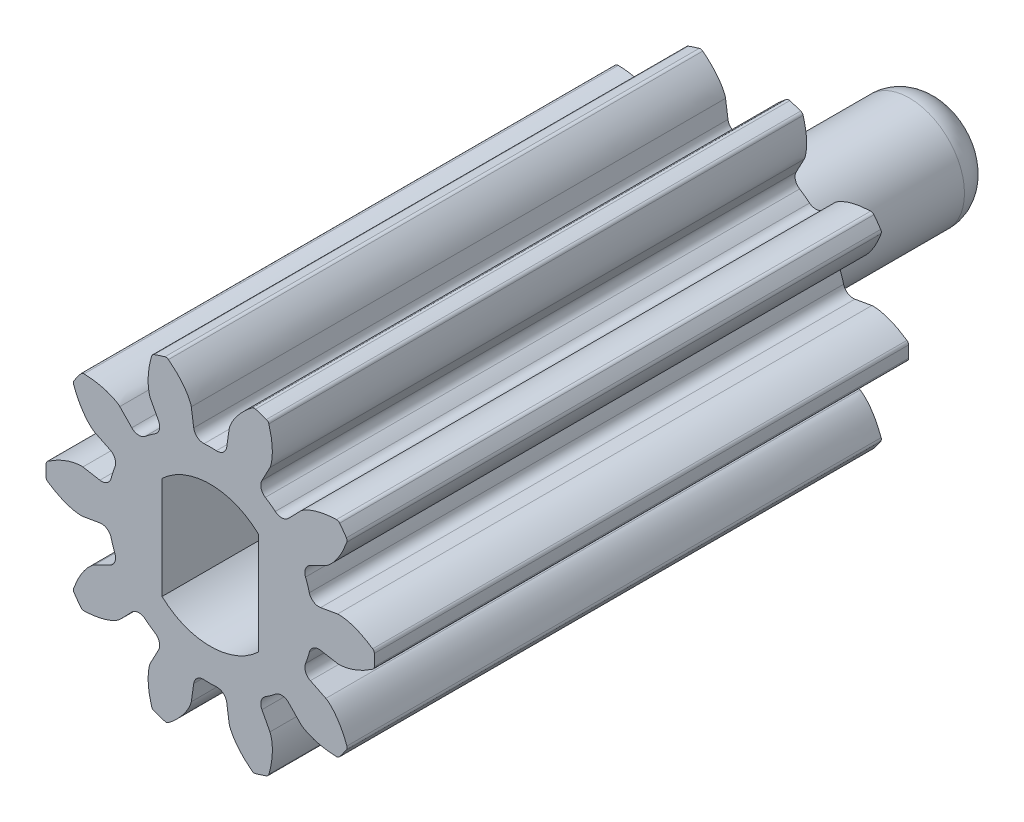
SolidWorks part; units mm, degrees
material "ABS"
ref_plane "Front" through (0, 0, 0) normal (0, 0, 1) x (1, 0, 0)
ref_plane "Top" through (0, 0, 0) normal (0, 1, 0) x (1, 0, 0)
ref_plane "Right" through (0, 0, 0) normal (1, 0, 0) x (0, 0, -1)
sketch "Sketch1" plane through (0, 0, 0) normal (0, 0, 1) x (1, 0, 0)
  circle A0 centre (0, 0) radius 6.35
extrude "Boss-Extrude1" add sketch "Sketch1" along normal blind 20.574
sketch "Sketch3" plane through (0, 0, 0) normal (0, 0, 1) x (1, 0, 0)
  line L0 (0, 0) -> (43.7181, 0) construction
  line L2 (0, 0) -> (-0.5624, 3.9287) construction
  line L3 (0, 0) -> (0.5624, 3.9287) construction
  line L4 (0.5624, 3.9287) -> (0.7046, 4.9224) construction
  line L5 (0, 0) -> (0, 61.276) construction
  line L6 (-0.5624, 3.9287) -> (-0.7046, 4.9224) construction
  circle A0 centre (0, 0) radius 6.35 construction
  circle A1 centre (0, 0) radius 5.2917 construction
  circle A2 centre (0, 0) radius 4.9725 construction
  arc A3 (0.5624, 3.9287) -> (-0.5624, 3.9287) centre (0, 0) ccw construction
  arc A5 (1.6642, 6.128) -> (-1.6642, 6.128) centre (0, 0) ccw
  spline S0 degree 4 poles (-0.7046, 4.9224) (-0.705, 4.9247) (-0.7061, 4.9311) (-0.7087, 4.9431) (-0.7137, 4.9626) (-0.721, 4.9872) (-0.7316, 5.0187) (-0.7454, 5.0554) (-0.7621, 5.0953) (-0.7818, 5.1381) (-0.8028, 5.1804) (-0.825, 5.2221) (-0.8483, 5.2631) (-0.8779, 5.3122) (-0.9151, 5.3703) (-0.9613, 5.437) (-1.0167, 5.511) (-1.0764, 5.5846) (-1.1378, 5.6556) (-1.2027, 5.7255) (-1.2676, 5.7919) (-1.338, 5.8588) (-1.4044, 5.9196) (-1.4819, 5.9855) (-1.5453, 6.0379) (-1.6323, 6.1046) (-1.6846, 6.1433) (-1.7469, 6.1876) (-1.7752, 6.2068) (-1.7925, 6.2186) knots 0 0 0 0 0 0.005377 0.015084 0.028532 0.04661 0.064855 0.092111 0.119476 0.146842 0.174209 0.201575 0.228941 0.256307 0.307035 0.361767 0.4165 0.471232 0.525964 0.580697 0.635429 0.690161 0.744894 0.799626 0.854358 0.909091 0.954545 1 1 1 1 1 construction
  spline S1 degree 4 poles (-0.7046, 4.9224) (-0.705, 4.9247) (-0.7061, 4.9311) (-0.7087, 4.9431) (-0.7137, 4.9626) (-0.721, 4.9872) (-0.7316, 5.0187) (-0.7454, 5.0554) (-0.7621, 5.0953) (-0.7818, 5.1381) (-0.8028, 5.1804) (-0.825, 5.2221) (-0.8483, 5.2631) (-0.8779, 5.3122) (-0.9151, 5.3703) (-0.9613, 5.437) (-1.0167, 5.511) (-1.0764, 5.5846) (-1.1378, 5.6556) (-1.2027, 5.7255) (-1.2676, 5.7919) (-1.338, 5.8588) (-1.4044, 5.9196) (-1.4819, 5.9855) (-1.5453, 6.0379) (-1.6134, 6.0902) (-1.647, 6.1153) (-1.6642, 6.128) knots 0 0 0 0 0 0.005377 0.015084 0.028532 0.04661 0.064855 0.092111 0.119476 0.146842 0.174209 0.201575 0.228941 0.256307 0.307035 0.361767 0.4165 0.471232 0.525964 0.580697 0.635429 0.690161 0.744894 0.799626 0.854358 0.909091 0.909091 0.909091 0.909091 0.909091
  spline S2 degree 4 poles (0.7046, 4.9224) (0.705, 4.9247) (0.7061, 4.9311) (0.7087, 4.9431) (0.7137, 4.9626) (0.721, 4.9872) (0.7316, 5.0187) (0.7454, 5.0554) (0.7621, 5.0953) (0.7818, 5.1381) (0.8028, 5.1804) (0.825, 5.2221) (0.8483, 5.2631) (0.8779, 5.3122) (0.9151, 5.3703) (0.9613, 5.437) (1.0167, 5.511) (1.0764, 5.5846) (1.1378, 5.6556) (1.2027, 5.7255) (1.2676, 5.7919) (1.338, 5.8588) (1.4044, 5.9196) (1.4819, 5.9855) (1.5453, 6.0379) (1.6323, 6.1046) (1.6846, 6.1433) (1.7469, 6.1876) (1.7752, 6.2068) (1.7925, 6.2186) knots 0 0 0 0 0 0.005377 0.015084 0.028532 0.04661 0.064855 0.092111 0.119476 0.146842 0.174209 0.201575 0.228941 0.256307 0.307035 0.361767 0.4165 0.471232 0.525964 0.580697 0.635429 0.690161 0.744894 0.799626 0.854358 0.909091 0.954545 1 1 1 1 1 construction
  spline S3 degree 4 poles (0.7046, 4.9224) (0.705, 4.9247) (0.7061, 4.9311) (0.7087, 4.9431) (0.7137, 4.9626) (0.721, 4.9872) (0.7316, 5.0187) (0.7454, 5.0554) (0.7621, 5.0953) (0.7818, 5.1381) (0.8028, 5.1804) (0.825, 5.2221) (0.8483, 5.2631) (0.8779, 5.3122) (0.9151, 5.3703) (0.9613, 5.437) (1.0167, 5.511) (1.0764, 5.5846) (1.1378, 5.6556) (1.2027, 5.7255) (1.2676, 5.7919) (1.338, 5.8588) (1.4044, 5.9196) (1.4819, 5.9855) (1.5453, 6.0379) (1.6134, 6.0902) (1.647, 6.1153) (1.6642, 6.128) knots 0 0 0 0 0 0.005377 0.015084 0.028532 0.04661 0.064855 0.092111 0.119476 0.146842 0.174209 0.201575 0.228941 0.256307 0.307035 0.361767 0.4165 0.471232 0.525964 0.580697 0.635429 0.690161 0.744894 0.799626 0.854358 0.909091 0.909091 0.909091 0.909091 0.909091
  point P0 (0, 3.9688)
sketch "DCLTBC" plane through (0, 0, 0) normal (0, 0, 1) x (1, 0, 0)
  line L0 (0, 0) -> (41.04, 0) construction
  line L1 (-0.5624, 3.9287) -> (-0.7046, 4.9224) construction
  line L2 (0.5624, 3.9287) -> (0.7046, 4.9224) construction
  line L3 (-0.5624, 3.9287) -> (-0.7046, 4.9224)
  line L4 (0.5624, 3.9287) -> (0.7046, 4.9224)
  line L5 (0, 0) -> (0, 104.9356) construction
  circle A0 centre (0, 0) radius 6.35
  circle A1 centre (0, 0) radius 5.2917 construction
  circle A2 centre (0, 0) radius 4.9725 construction
  arc A3 (0.5624, 3.9287) -> (-0.5624, 3.9287) centre (0, 0) ccw construction
  arc A4 (0.5624, 3.9287) -> (-0.5624, 3.9287) centre (0, 0) ccw
  spline S0 degree 4 poles (-988.7588, -149.038) (-11.8151, 2.4708) (-0.7866, 4.3496) (-0.6413, 4.6789) (-0.7137, 4.9626) (-0.721, 4.9872) (-0.7316, 5.0187) (-0.7454, 5.0554) (-0.7621, 5.0953) (-0.7818, 5.1381) (-0.8028, 5.1804) (-0.825, 5.2221) (-0.8483, 5.2631) (-0.8779, 5.3122) (-0.9151, 5.3703) (-0.9613, 5.437) (-1.0167, 5.511) (-1.0764, 5.5846) (-1.1378, 5.6556) (-1.2027, 5.7255) (-1.2676, 5.7919) (-1.338, 5.8588) (-1.4044, 5.9196) (-1.4819, 5.9855) (-1.8387, 6.2805) (-3.231, 7.2231) (17.05, -7.85) (-807.2758, 598.5552) knots -0.632257 -0.632257 -0.632257 -0.632257 -0.632257 0.005377 0.015084 0.028532 0.04661 0.064855 0.092111 0.119476 0.146842 0.174209 0.201575 0.228941 0.256307 0.307035 0.361767 0.4165 0.471232 0.525964 0.580697 0.635429 0.690161 0.744894 0.799626 0.854358 1.920904 1.920904 1.920904 1.920904 1.920904 only from (-0.7046, 4.9224) to (-1.6642, 6.128) construction
  spline S1 degree 4 poles (988.7588, -149.038) (11.8151, 2.4708) (0.7866, 4.3496) (0.6413, 4.6789) (0.7137, 4.9626) (0.721, 4.9872) (0.7316, 5.0187) (0.7454, 5.0554) (0.7621, 5.0953) (0.7818, 5.1381) (0.8028, 5.1804) (0.825, 5.2221) (0.8483, 5.2631) (0.8779, 5.3122) (0.9151, 5.3703) (0.9613, 5.437) (1.0167, 5.511) (1.0764, 5.5846) (1.1378, 5.6556) (1.2027, 5.7255) (1.2676, 5.7919) (1.338, 5.8588) (1.4044, 5.9196) (1.4819, 5.9855) (1.8387, 6.2805) (3.231, 7.2231) (-17.05, -7.85) (807.2758, 598.5552) knots -0.632257 -0.632257 -0.632257 -0.632257 -0.632257 0.005377 0.015084 0.028532 0.04661 0.064855 0.092111 0.119476 0.146842 0.174209 0.201575 0.228941 0.256307 0.307035 0.361767 0.4165 0.471232 0.525964 0.580697 0.635429 0.690161 0.744894 0.799626 0.854358 1.920904 1.920904 1.920904 1.920904 1.920904 only from (0.7046, 4.9224) to (1.6642, 6.128) construction
  spline S2 degree 4 poles (-0.7046, 4.9224) (-0.705, 4.9247) (-0.7061, 4.9311) (-0.7087, 4.9431) (-0.7137, 4.9626) (-0.721, 4.9872) (-0.7316, 5.0187) (-0.7454, 5.0554) (-0.7621, 5.0953) (-0.7818, 5.1381) (-0.8028, 5.1804) (-0.825, 5.2221) (-0.8483, 5.2631) (-0.8779, 5.3122) (-0.9151, 5.3703) (-0.9613, 5.437) (-1.0167, 5.511) (-1.0764, 5.5846) (-1.1378, 5.6556) (-1.2027, 5.7255) (-1.2676, 5.7919) (-1.338, 5.8588) (-1.4044, 5.9196) (-1.4819, 5.9855) (-1.5453, 6.0379) (-1.6134, 6.0902) (-1.647, 6.1153) (-1.6642, 6.128) knots 0 0 0 0 0 0.005377 0.015084 0.028532 0.04661 0.064855 0.092111 0.119476 0.146842 0.174209 0.201575 0.228941 0.256307 0.307035 0.361767 0.4165 0.471232 0.525964 0.580697 0.635429 0.690161 0.744894 0.799626 0.854358 0.909091 0.909091 0.909091 0.909091 0.909091
  spline S3 degree 4 poles (0.7046, 4.9224) (0.705, 4.9247) (0.7061, 4.9311) (0.7087, 4.9431) (0.7137, 4.9626) (0.721, 4.9872) (0.7316, 5.0187) (0.7454, 5.0554) (0.7621, 5.0953) (0.7818, 5.1381) (0.8028, 5.1804) (0.825, 5.2221) (0.8483, 5.2631) (0.8779, 5.3122) (0.9151, 5.3703) (0.9613, 5.437) (1.0167, 5.511) (1.0764, 5.5846) (1.1378, 5.6556) (1.2027, 5.7255) (1.2676, 5.7919) (1.338, 5.8588) (1.4044, 5.9196) (1.4819, 5.9855) (1.5453, 6.0379) (1.6134, 6.0902) (1.647, 6.1153) (1.6642, 6.128) knots 0 0 0 0 0 0.005377 0.015084 0.028532 0.04661 0.064855 0.092111 0.119476 0.146842 0.174209 0.201575 0.228941 0.256307 0.307035 0.361767 0.4165 0.471232 0.525964 0.580697 0.635429 0.690161 0.744894 0.799626 0.854358 0.909091 0.909091 0.909091 0.909091 0.909091
extrude "Cut-Extrude-DCLTBC" cut sketch "DCLTBC" along normal through all
fillet "Fillet-Tip-DCLTBC" radius 0.1775 2 edges at (1.6642, 6.128, 10.287) (-1.6642, 6.128, 10.287)
fillet "Fillet-Root-DCLTBC" radius 0.3551 2 edges at (-0.5624, 3.9287, 10.287) (0.5624, 3.9287, 10.287)
pattern_circular "CirPattern-DCLTBC" count 10 over 360 about axis through (0, 0, 20.574) along (0, 0, 1) of "Cut-Extrude-DCLTBC", "Fillet-Tip-DCLTBC", "Fillet-Root-DCLTBC"
sketch "DCGTBC" [suppressed] plane through (0, 0, 0) normal (0, 0, 1) x (1, 0, 0)
  line L0 (0, 0) -> (41.04, 0) construction
  line L1 (-22.6634, 1.9828) -> (0, 0) construction
  line L2 (0, 0) -> (22.6634, 1.9828) construction
  line L3 (0, 0) -> (-16.5124, 0)
  line L5 (0, 0) -> (0, 104.9356) construction
  circle A0 centre (0, 0) radius 25
  circle A1 centre (0, 0) radius 24 construction
  circle A2 centre (0, 0) radius 21.7514 construction
  arc A3 (0.0626, 22.7499) -> (-0.0626, 22.7499) centre (0, 0) ccw construction
  arc A11 (22.6634, 1.9828) -> (-22.6634, 1.9828) centre (0, 0) ccw
  spline S4 degree 4 poles (999.7589, -2.0808) (12.8658, 20.0937) (0.2547, 20.6746) (0.0189, 21.2606) (0.0654, 21.8429) (0.0715, 21.8997) (0.0812, 21.973) (0.095, 22.0592) (0.1126, 22.1539) (0.1343, 22.2566) (0.1583, 22.3589) (0.1845, 22.4607) (0.2124, 22.562) (0.2486, 22.6844) (0.2952, 22.8308) (0.3543, 23.0013) (0.4268, 23.1939) (0.5065, 23.3893) (0.5897, 23.5809) (0.6793, 23.7735) (0.7698, 23.9592) (0.8695, 24.151) (0.9643, 24.3275) (1.0767, 24.524) (1.517, 25.277) (3.0654, 27.5692) (-13.787, 0.9944) (540.7091, 867.0187) knots -0.561807 -0.561807 -0.561807 -0.561807 -0.561807 0.005377 0.015084 0.028532 0.04661 0.064855 0.092111 0.119476 0.146842 0.174209 0.201575 0.228941 0.256307 0.307035 0.361767 0.4165 0.471232 0.525964 0.580697 0.635429 0.690161 0.744894 0.799626 0.854358 1.731906 1.731906 1.731906 1.731906 1.731906 only from (0.0598, 21.7513) to (1.3455, 24.9638) construction
  spline S5 degree 4 poles (-999.7589, -2.0808) (-12.8658, 20.0937) (-0.2547, 20.6746) (-0.0189, 21.2606) (-0.0654, 21.8429) (-0.0715, 21.8997) (-0.0812, 21.973) (-0.095, 22.0592) (-0.1126, 22.1539) (-0.1343, 22.2566) (-0.1583, 22.3589) (-0.1845, 22.4607) (-0.2124, 22.562) (-0.2486, 22.6844) (-0.2952, 22.8308) (-0.3543, 23.0013) (-0.4268, 23.1939) (-0.5065, 23.3893) (-0.5897, 23.5809) (-0.6793, 23.7735) (-0.7698, 23.9592) (-0.8695, 24.151) (-0.9643, 24.3275) (-1.0767, 24.524) (-1.517, 25.277) (-3.0654, 27.5692) (13.787, 0.9944) (-540.7091, 867.0187) knots -0.561807 -0.561807 -0.561807 -0.561807 -0.561807 0.005377 0.015084 0.028532 0.04661 0.064855 0.092111 0.119476 0.146842 0.174209 0.201575 0.228941 0.256307 0.307035 0.361767 0.4165 0.471232 0.525964 0.580697 0.635429 0.690161 0.744894 0.799626 0.854358 1.731906 1.731906 1.731906 1.731906 1.731906 only from (-0.0598, 21.7513) to (-1.3455, 24.9638) construction
  spline S6 degree 4 poles (0.0598, 21.7513) (0.0599, 21.7565) (0.0603, 21.7709) (0.0618, 21.7983) (0.0654, 21.8429) (0.0715, 21.8997) (0.0812, 21.973) (0.095, 22.0592) (0.1126, 22.1539) (0.1343, 22.2566) (0.1583, 22.3589) (0.1845, 22.4607) (0.2124, 22.562) (0.2486, 22.6844) (0.2952, 22.8308) (0.3543, 23.0013) (0.4268, 23.1939) (0.5065, 23.3893) (0.5897, 23.5809) (0.6793, 23.7735) (0.7698, 23.9592) (0.8695, 24.151) (0.9643, 24.3275) (1.0767, 24.524) (1.1693, 24.6823) (1.27, 24.8447) (1.3197, 24.9235) (1.3455, 24.9638) knots 0 0 0 0 0 0.005377 0.015084 0.028532 0.04661 0.064855 0.092111 0.119476 0.146842 0.174209 0.201575 0.228941 0.256307 0.307035 0.361767 0.4165 0.471232 0.525964 0.580697 0.635429 0.690161 0.744894 0.799626 0.854358 0.909091 0.909091 0.909091 0.909091 0.909091
  spline S7 degree 4 poles (-0.0598, 21.7513) (-0.0599, 21.7565) (-0.0603, 21.7709) (-0.0618, 21.7983) (-0.0654, 21.8429) (-0.0715, 21.8997) (-0.0812, 21.973) (-0.095, 22.0592) (-0.1126, 22.1539) (-0.1343, 22.2566) (-0.1583, 22.3589) (-0.1845, 22.4607) (-0.2124, 22.562) (-0.2486, 22.6844) (-0.2952, 22.8308) (-0.3543, 23.0013) (-0.4268, 23.1939) (-0.5065, 23.3893) (-0.5897, 23.5809) (-0.6793, 23.7735) (-0.7698, 23.9592) (-0.8695, 24.151) (-0.9643, 24.3275) (-1.0767, 24.524) (-1.1693, 24.6823) (-1.27, 24.8447) (-1.3197, 24.9235) (-1.3455, 24.9638) knots 0 0 0 0 0 0.005377 0.015084 0.028532 0.04661 0.064855 0.092111 0.119476 0.146842 0.174209 0.201575 0.228941 0.256307 0.307035 0.361767 0.4165 0.471232 0.525964 0.580697 0.635429 0.690161 0.744894 0.799626 0.854358 0.909091 0.909091 0.909091 0.909091 0.909091
  dimension "D1" = 5
  dimension "D2" = 5
extrude "Cut-Extrude-DCGTBC" [suppressed] cut sketch "DCGTBC" along normal through all
fillet "Fillet-Tip-DCGTBC" [suppressed] radius 0.1775
pattern_circular "CirPattern-DCGTBC" [suppressed] count 10 over 360
sketch "Sketch4" plane through (0, 0, 20.574) normal (0, 0, 1) x (1, 0, 0)
  circle A1 centre (0, 0) radius 2.7051
  dimension "D1" = 5.4102
extrude "Cut-Extrude2" cut sketch "Sketch4" against normal through all
sketch "Sketch5" plane through (0, 0, 20.574) normal (0, 0, 1) x (1, 0, 0)
  line L0 (-1.8542, 1.9696) -> (-1.8542, -1.9696)
  line L1 (1.8542, 1.9696) -> (1.8542, -1.9696)
  circle A0 centre (0, 0) radius 2.7051 construction
  circle A1 centre (0, 0) radius 2.7051
  dimension "D1" = 3.7084
extrude "Boss-Extrude2" add sketch "Sketch5" against normal through all contours L0 A1 | L1 A1
sketch "Sketch6" plane through (0, 0, 0) normal (0, 0, -1) x (-1, 0, 0)
  line L4 (-1.9655, 2.0878) -> (-1.9655, -2.0878)
  line L5 (1.9655, -2.0878) -> (1.9655, 2.0878)
  arc A4 (-1.9655, -2.0878) -> (1.9655, -2.0878) centre (0, 0) ccw
  arc A5 (1.9655, 2.0878) -> (-1.9655, 2.0878) centre (0, 0) ccw
extrude "Boss-Extrude3" add sketch "Sketch6" against normal blind 3.175
sketch "Sketch7" plane through (0, 0, 0) normal (0, 0, -1) x (-1, 0, 0)
  circle A0 centre (0, 0) radius 2.1209
  dimension "D1" = 4.2418
extrude "Boss-Extrude4" add sketch "Sketch7" along normal blind 7.62
fillet "Fillet1" radius 1.27 1 edges at (-2.1209, 0, -7.62)
sketch "Sketch8" plane through (0, 0, 20.574) normal (0, 0, 1) x (1, 0, 0)
  line L50 (0.7297, 4.9185) -> (0.6357, 4.2621)
  line L51 (-0.6357, 4.2621) -> (-0.7297, 4.9185)
  line L52 (-2.3007, 4.4081) -> (-1.9909, 3.8218)
  line L53 (-3.0196, 3.0745) -> (-3.4814, 3.5503)
  line L54 (-4.4523, 2.2139) -> (-3.8571, 1.9217)
  line L55 (-4.25, 0.7124) -> (-4.9033, 0.8259)
  line L56 (-4.9033, -0.8259) -> (-4.25, -0.7124)
  line L57 (-3.8571, -1.9217) -> (-4.4523, -2.2139)
  line L58 (-3.4814, -3.5503) -> (-3.0196, -3.0745)
  line L59 (-1.9909, -3.8218) -> (-2.3007, -4.4081)
  line L60 (-0.7297, -4.9185) -> (-0.6357, -4.2621)
  line L61 (0.6357, -4.2621) -> (0.7297, -4.9185)
  line L62 (2.3007, -4.4081) -> (1.9909, -3.8218)
  line L63 (3.0196, -3.0745) -> (3.4814, -3.5503)
  line L64 (4.4523, -2.2139) -> (3.8571, -1.9217)
  line L65 (4.25, -0.7124) -> (4.9033, -0.8259)
  line L66 (4.9033, 0.8259) -> (4.25, 0.7124)
  line L67 (3.8571, 1.9217) -> (4.4523, 2.2139)
  line L68 (3.4814, 3.5503) -> (3.0196, 3.0745)
  line L69 (1.9909, 3.8218) -> (2.3007, 4.4081)
  line L74 (0.7297, 4.9185) -> (0.6357, 4.2621)
  line L75 (-0.6357, 4.2621) -> (-0.7297, 4.9185)
  line L76 (-2.3007, 4.4081) -> (-1.9909, 3.8218)
  line L77 (-3.0196, 3.0745) -> (-3.4814, 3.5503)
  line L78 (-4.4523, 2.2139) -> (-3.8571, 1.9217)
  line L79 (-4.25, 0.7124) -> (-4.9033, 0.8259)
  line L80 (-4.9033, -0.8259) -> (-4.25, -0.7124)
  line L81 (-3.8571, -1.9217) -> (-4.4523, -2.2139)
  line L82 (-3.4814, -3.5503) -> (-3.0196, -3.0745)
  line L83 (-1.9909, -3.8218) -> (-2.3007, -4.4081)
  line L84 (-0.7297, -4.9185) -> (-0.6357, -4.2621)
  line L85 (0.6357, -4.2621) -> (0.7297, -4.9185)
  line L86 (2.3007, -4.4081) -> (1.9909, -3.8218)
  line L87 (3.0196, -3.0745) -> (3.4814, -3.5503)
  line L88 (4.4523, -2.2139) -> (3.8571, -1.9217)
  line L89 (4.25, -0.7124) -> (4.9033, -0.8259)
  line L90 (4.9033, 0.8259) -> (4.25, 0.7124)
  line L91 (3.8571, 1.9217) -> (4.4523, 2.2139)
  line L92 (3.4814, 3.5503) -> (3.0196, 3.0745)
  line L93 (1.9909, 3.8218) -> (2.3007, 4.4081)
  arc A150 (2.1634, 5.9431) -> (1.743, 6.0797) centre (0, 0) ccw
  arc A151 (1.743, 6.0797) -> (1.6082, 6.054) centre (1.7011, 5.9334) ccw
  arc A152 (0.2363, 3.9363) -> (0.6357, 4.2621) centre (0.2591, 4.3161) ccw
  arc A153 (0.2363, 3.9363) -> (-0.2363, 3.9363) centre (0, 0) ccw
  arc A154 (-0.6357, 4.2621) -> (-0.2363, 3.9363) centre (-0.2591, 4.3161) ccw
  arc A155 (-1.6082, 6.054) -> (-1.743, 6.0797) centre (-1.7011, 5.9334) ccw
  arc A156 (-1.743, 6.0797) -> (-2.1634, 5.9431) centre (0, 0) ccw
  arc A157 (-2.1634, 5.9431) -> (-2.2573, 5.8431) centre (-2.1114, 5.8001) ccw
  arc A158 (-2.1225, 3.3234) -> (-1.9909, 3.8218) centre (-2.3273, 3.6441) ccw
  arc A159 (-2.1225, 3.3234) -> (-2.5049, 3.0456) centre (0, 0) ccw
  arc A160 (-3.0196, 3.0745) -> (-2.5049, 3.0456) centre (-2.7465, 3.3395) ccw
  arc A161 (-4.8595, 3.9525) -> (-4.9837, 3.894) centre (-4.8638, 3.8004) ccw
  arc A162 (-4.9837, 3.894) -> (-5.2435, 3.5364) centre (0, 0) ccw
  arc A163 (-5.2435, 3.5364) -> (-5.2607, 3.4003) centre (-5.1174, 3.4514) ccw
  arc A164 (-3.6706, 1.4411) -> (-3.8571, 1.9217) centre (-4.0247, 1.5802) ccw
  arc A165 (-3.6706, 1.4411) -> (-3.8166, 0.9916) centre (0, 0) ccw
  arc A166 (-4.25, 0.7124) -> (-3.8166, 0.9916) centre (-4.1849, 1.0873) ccw
  arc A167 (-6.2546, 0.3412) -> (-6.3207, 0.221) centre (-6.1687, 0.2157) ccw
  arc A168 (-6.3207, 0.221) -> (-6.3207, -0.221) centre (0, 0) ccw
  arc A169 (-6.3207, -0.221) -> (-6.2546, -0.3412) centre (-6.1687, -0.2157) ccw
  arc A170 (-3.8166, -0.9916) -> (-4.25, -0.7124) centre (-4.1849, -1.0873) ccw
  arc A171 (-3.8166, -0.9916) -> (-3.6706, -1.4411) centre (0, 0) ccw
  arc A172 (-3.8571, -1.9217) -> (-3.6706, -1.4411) centre (-4.0247, -1.5802) ccw
  arc A173 (-5.2607, -3.4003) -> (-5.2435, -3.5364) centre (-5.1174, -3.4514) ccw
  arc A174 (-5.2435, -3.5364) -> (-4.9837, -3.894) centre (0, 0) ccw
  arc A175 (-4.9837, -3.894) -> (-4.8595, -3.9525) centre (-4.8638, -3.8004) ccw
  arc A176 (-2.5049, -3.0456) -> (-3.0196, -3.0745) centre (-2.7465, -3.3395) ccw
  arc A177 (-2.5049, -3.0456) -> (-2.1225, -3.3234) centre (0, 0) ccw
  arc A178 (-1.9909, -3.8218) -> (-2.1225, -3.3234) centre (-2.3273, -3.6441) ccw
  arc A179 (-2.2573, -5.8431) -> (-2.1634, -5.9431) centre (-2.1114, -5.8001) ccw
  arc A180 (-2.1634, -5.9431) -> (-1.743, -6.0797) centre (0, 0) ccw
  arc A181 (-1.743, -6.0797) -> (-1.6082, -6.054) centre (-1.7011, -5.9334) ccw
  arc A182 (-0.2363, -3.9363) -> (-0.6357, -4.2621) centre (-0.2591, -4.3161) ccw
  arc A183 (-0.2363, -3.9363) -> (0.2363, -3.9363) centre (0, 0) ccw
  arc A184 (0.6357, -4.2621) -> (0.2363, -3.9363) centre (0.2591, -4.3161) ccw
  arc A185 (1.6082, -6.054) -> (1.743, -6.0797) centre (1.7011, -5.9334) ccw
  arc A186 (1.743, -6.0797) -> (2.1634, -5.9431) centre (0, 0) ccw
  arc A187 (2.1634, -5.9431) -> (2.2573, -5.8431) centre (2.1114, -5.8001) ccw
  arc A188 (2.1225, -3.3234) -> (1.9909, -3.8218) centre (2.3273, -3.6441) ccw
  arc A189 (2.1225, -3.3234) -> (2.5049, -3.0456) centre (0, 0) ccw
  arc A190 (3.0196, -3.0745) -> (2.5049, -3.0456) centre (2.7465, -3.3395) ccw
  arc A191 (4.8595, -3.9525) -> (4.9837, -3.894) centre (4.8638, -3.8004) ccw
  arc A192 (4.9837, -3.894) -> (5.2435, -3.5364) centre (0, 0) ccw
  arc A193 (5.2435, -3.5364) -> (5.2607, -3.4003) centre (5.1174, -3.4514) ccw
  arc A194 (3.6706, -1.4411) -> (3.8571, -1.9217) centre (4.0247, -1.5802) ccw
  arc A195 (3.6706, -1.4411) -> (3.8166, -0.9916) centre (0, 0) ccw
  arc A196 (4.25, -0.7124) -> (3.8166, -0.9916) centre (4.1849, -1.0873) ccw
  arc A197 (6.2546, -0.3412) -> (6.3207, -0.221) centre (6.1687, -0.2157) ccw
  arc A198 (6.3207, -0.221) -> (6.3207, 0.221) centre (0, 0) ccw
  arc A199 (6.3207, 0.221) -> (6.2546, 0.3412) centre (6.1687, 0.2157) ccw
  arc A200 (3.8166, 0.9916) -> (4.25, 0.7124) centre (4.1849, 1.0873) ccw
  arc A201 (3.8166, 0.9916) -> (3.6706, 1.4411) centre (0, 0) ccw
  arc A202 (3.8571, 1.9217) -> (3.6706, 1.4411) centre (4.0247, 1.5802) ccw
  arc A203 (5.2607, 3.4003) -> (5.2435, 3.5364) centre (5.1174, 3.4514) ccw
  arc A204 (5.2435, 3.5364) -> (4.9837, 3.894) centre (0, 0) ccw
  arc A205 (4.9837, 3.894) -> (4.8595, 3.9525) centre (4.8638, 3.8004) ccw
  arc A206 (2.5049, 3.0456) -> (3.0196, 3.0745) centre (2.7465, 3.3395) ccw
  arc A207 (2.5049, 3.0456) -> (2.1225, 3.3234) centre (0, 0) ccw
  arc A208 (1.9909, 3.8218) -> (2.1225, 3.3234) centre (2.3273, 3.6441) ccw
  arc A209 (2.2573, 5.8431) -> (2.1634, 5.9431) centre (2.1114, 5.8001) ccw
  arc A222 (2.1634, 5.9431) -> (1.743, 6.0797) centre (0, 0) ccw
  arc A223 (1.743, 6.0797) -> (1.6082, 6.054) centre (1.7011, 5.9334) ccw
  arc A224 (0.2363, 3.9363) -> (0.6357, 4.2621) centre (0.2591, 4.3161) ccw
  arc A225 (0.2363, 3.9363) -> (-0.2363, 3.9363) centre (0, 0) ccw
  arc A226 (-0.6357, 4.2621) -> (-0.2363, 3.9363) centre (-0.2591, 4.3161) ccw
  arc A227 (-1.6082, 6.054) -> (-1.743, 6.0797) centre (-1.7011, 5.9334) ccw
  arc A228 (-1.743, 6.0797) -> (-2.1634, 5.9431) centre (0, 0) ccw
  arc A229 (-2.1634, 5.9431) -> (-2.2573, 5.8431) centre (-2.1114, 5.8001) ccw
  arc A230 (-2.1225, 3.3234) -> (-1.9909, 3.8218) centre (-2.3273, 3.6441) ccw
  arc A231 (-2.1225, 3.3234) -> (-2.5049, 3.0456) centre (0, 0) ccw
  arc A232 (-3.0196, 3.0745) -> (-2.5049, 3.0456) centre (-2.7465, 3.3395) ccw
  arc A233 (-4.8595, 3.9525) -> (-4.9837, 3.894) centre (-4.8638, 3.8004) ccw
  arc A234 (-4.9837, 3.894) -> (-5.2435, 3.5364) centre (0, 0) ccw
  arc A235 (-5.2435, 3.5364) -> (-5.2607, 3.4003) centre (-5.1174, 3.4514) ccw
  arc A236 (-3.6706, 1.4411) -> (-3.8571, 1.9217) centre (-4.0247, 1.5802) ccw
  arc A237 (-3.6706, 1.4411) -> (-3.8166, 0.9916) centre (0, 0) ccw
  arc A238 (-4.25, 0.7124) -> (-3.8166, 0.9916) centre (-4.1849, 1.0873) ccw
  arc A239 (-6.2546, 0.3412) -> (-6.3207, 0.221) centre (-6.1687, 0.2157) ccw
  arc A240 (-6.3207, 0.221) -> (-6.3207, -0.221) centre (0, 0) ccw
  arc A241 (-6.3207, -0.221) -> (-6.2546, -0.3412) centre (-6.1687, -0.2157) ccw
  arc A242 (-3.8166, -0.9916) -> (-4.25, -0.7124) centre (-4.1849, -1.0873) ccw
  arc A243 (-3.8166, -0.9916) -> (-3.6706, -1.4411) centre (0, 0) ccw
  arc A244 (-3.8571, -1.9217) -> (-3.6706, -1.4411) centre (-4.0247, -1.5802) ccw
  arc A245 (-5.2607, -3.4003) -> (-5.2435, -3.5364) centre (-5.1174, -3.4514) ccw
  arc A246 (-5.2435, -3.5364) -> (-4.9837, -3.894) centre (0, 0) ccw
  arc A247 (-4.9837, -3.894) -> (-4.8595, -3.9525) centre (-4.8638, -3.8004) ccw
  arc A248 (-2.5049, -3.0456) -> (-3.0196, -3.0745) centre (-2.7465, -3.3395) ccw
  arc A249 (-2.5049, -3.0456) -> (-2.1225, -3.3234) centre (0, 0) ccw
  arc A250 (-1.9909, -3.8218) -> (-2.1225, -3.3234) centre (-2.3273, -3.6441) ccw
  arc A251 (-2.2573, -5.8431) -> (-2.1634, -5.9431) centre (-2.1114, -5.8001) ccw
  arc A252 (-2.1634, -5.9431) -> (-1.743, -6.0797) centre (0, 0) ccw
  arc A253 (-1.743, -6.0797) -> (-1.6082, -6.054) centre (-1.7011, -5.9334) ccw
  arc A254 (-0.2363, -3.9363) -> (-0.6357, -4.2621) centre (-0.2591, -4.3161) ccw
  arc A255 (-0.2363, -3.9363) -> (0.2363, -3.9363) centre (0, 0) ccw
  arc A256 (0.6357, -4.2621) -> (0.2363, -3.9363) centre (0.2591, -4.3161) ccw
  arc A257 (1.6082, -6.054) -> (1.743, -6.0797) centre (1.7011, -5.9334) ccw
  arc A258 (1.743, -6.0797) -> (2.1634, -5.9431) centre (0, 0) ccw
  arc A259 (2.1634, -5.9431) -> (2.2573, -5.8431) centre (2.1114, -5.8001) ccw
  arc A260 (2.1225, -3.3234) -> (1.9909, -3.8218) centre (2.3273, -3.6441) ccw
  arc A261 (2.1225, -3.3234) -> (2.5049, -3.0456) centre (0, 0) ccw
  arc A262 (3.0196, -3.0745) -> (2.5049, -3.0456) centre (2.7465, -3.3395) ccw
  arc A263 (4.8595, -3.9525) -> (4.9837, -3.894) centre (4.8638, -3.8004) ccw
  arc A264 (4.9837, -3.894) -> (5.2435, -3.5364) centre (0, 0) ccw
  arc A265 (5.2435, -3.5364) -> (5.2607, -3.4003) centre (5.1174, -3.4514) ccw
  arc A266 (3.6706, -1.4411) -> (3.8571, -1.9217) centre (4.0247, -1.5802) ccw
  arc A267 (3.6706, -1.4411) -> (3.8166, -0.9916) centre (0, 0) ccw
  arc A268 (4.25, -0.7124) -> (3.8166, -0.9916) centre (4.1849, -1.0873) ccw
  arc A269 (6.2546, -0.3412) -> (6.3207, -0.221) centre (6.1687, -0.2157) ccw
  arc A270 (6.3207, -0.221) -> (6.3207, 0.221) centre (0, 0) ccw
  arc A271 (6.3207, 0.221) -> (6.2546, 0.3412) centre (6.1687, 0.2157) ccw
  arc A272 (3.8166, 0.9916) -> (4.25, 0.7124) centre (4.1849, 1.0873) ccw
  arc A273 (3.8166, 0.9916) -> (3.6706, 1.4411) centre (0, 0) ccw
  arc A274 (3.8571, 1.9217) -> (3.6706, 1.4411) centre (4.0247, 1.5802) ccw
  arc A275 (5.2607, 3.4003) -> (5.2435, 3.5364) centre (5.1174, 3.4514) ccw
  arc A276 (5.2435, 3.5364) -> (4.9837, 3.894) centre (0, 0) ccw
  arc A277 (4.9837, 3.894) -> (4.8595, 3.9525) centre (4.8638, 3.8004) ccw
  arc A278 (2.5049, 3.0456) -> (3.0196, 3.0745) centre (2.7465, 3.3395) ccw
  arc A279 (2.5049, 3.0456) -> (2.1225, 3.3234) centre (0, 0) ccw
  arc A280 (1.9909, 3.8218) -> (2.1225, 3.3234) centre (2.3273, 3.6441) ccw
  arc A281 (2.2573, 5.8431) -> (2.1634, 5.9431) centre (2.1114, 5.8001) ccw
  spline S50 degree 3 poles (-2981.1226, 322.9869) (138.6336, -64.8997) (11.7316, 18.4787) (1.005, 5.4571) (0.9336, 5.3577) (0.8415, 5.2008) (0.8133, 5.1471) (0.7762, 5.0638) (0.7647, 5.0354) (-0.1197, 2.5272) (1.8075, -0.8005) (2869.2547, -871.9201) knots -33.999078 -33.999078 -33.999078 -33.999078 0.5 0.5 0.75 0.75 0.875 0.875 0.9375 0.9375 6.320462 6.320462 6.320462 6.320462 only from (1.6082, 6.054) to (0.7297, 4.9185)
  spline S51 degree 3 poles (-2814.1262, -1035.4767) (-1.5149, -0.8224) (0.1127, 2.55) (-0.7648, 5.0357) (-0.7763, 5.0639) (-0.8136, 5.1477) (-0.8422, 5.202) (-0.9344, 5.359) (-1.005, 5.4571) (-11.3131, 17.9741) (-133.6801, -53.9624) (2992.326, -173.0623) knots -5.275059 -5.275059 -5.275059 -5.275059 0.0625 0.0625 0.125 0.125 0.25 0.25 0.5 0.5 33.744281 33.744281 33.744281 33.744281 only from (-0.7297, 4.9185) to (-1.6082, 6.054)
  spline S52 degree 3 poles (-2601.6258, -1490.958) (150.3041, 28.9818) (-1.3704, 21.8453) (-2.3945, 5.0056) (-2.3939, 4.8833) (-2.3761, 4.7021) (-2.3674, 4.6421) (-2.3484, 4.5529) (-2.3411, 4.5232) (-1.5823, 1.9742) (1.9329, 0.4148) (2833.7776, 981.1074) knots -33.999078 -33.999078 -33.999078 -33.999078 0.5 0.5 0.75 0.75 0.875 0.875 0.9375 0.9375 6.320462 6.320462 6.320462 6.320462 only from (-2.2573, 5.8431) to (-2.3007, 4.4081)
  spline S53 degree 3 poles (-1668.038, -2491.8202) (-0.7422, -1.5558) (-1.4076, 2.1292) (-3.5786, 3.6244) (-3.6045, 3.6405) (-3.684, 3.6864) (-3.739, 3.7135) (-3.9059, 3.7863) (-4.0207, 3.8242) (-19.7174, 7.8917) (-76.4312, -122.2317) (2522.566, 1618.8348) knots -5.275059 -5.275059 -5.275059 -5.275059 0.0625 0.0625 0.125 0.125 0.25 0.25 0.5 0.5 33.744281 33.744281 33.744281 33.744281 only from (-3.4814, 3.5503) to (-4.8595, 3.9525)
  spline S54 degree 3 poles (-1228.3963, -2735.4076) (104.5635, 111.7933) (-13.949, 16.8677) (-4.8795, 2.6422) (-4.807, 2.5435) (-4.6862, 2.4075) (-4.6439, 2.364) (-4.5761, 2.303) (-4.5526, 2.2833) (-2.4405, 0.6671) (1.3199, 1.4717) (1715.8938, 2459.3853) knots -33.999078 -33.999078 -33.999078 -33.999078 0.5 0.5 0.75 0.75 0.875 0.875 0.9375 0.9375 6.320462 6.320462 6.320462 6.320462 only from (-5.2607, 3.4003) to (-4.4523, 2.2139)
  spline S55 degree 3 poles (115.1841, -2996.373) (0.314, -1.6949) (-2.3903, 0.8952) (-5.0255, 0.8287) (-5.056, 0.8266) (-5.1472, 0.817) (-5.2077, 0.8065) (-5.3855, 0.7673) (-5.5006, 0.7305) (-20.5904, -5.2051) (10.0118, -143.8127) (1089.2716, 2792.3919) knots -5.275059 -5.275059 -5.275059 -5.275059 0.0625 0.0625 0.125 0.125 0.25 0.25 0.5 0.5 33.744281 33.744281 33.744281 33.744281 only from (-4.9033, 0.8259) to (-6.2546, 0.3412)
  spline S56 degree 3 poles (614.0388, -2935.0245) (18.8832, 151.9035) (-21.1996, 5.4472) (-5.5006, -0.7305) (-5.384, -0.7677) (-5.2063, -0.8068) (-5.1465, -0.8171) (-5.0558, -0.8266) (-5.0253, -0.8288) (-2.3666, -0.8948) (0.2028, 1.9664) (-57.4032, 2998.2615) knots -33.999078 -33.999078 -33.999078 -33.999078 0.5 0.5 0.75 0.75 0.875 0.875 0.9375 0.9375 6.320462 6.320462 6.320462 6.320462 only from (-6.2546, -0.3412) to (-4.9033, -0.8259)
  spline S57 degree 3 poles (1854.4097, -2356.4131) (1.2503, -1.1867) (-2.46, -0.6808) (-4.5529, -2.2835) (-4.5762, -2.3031) (-4.6444, -2.3645) (-4.6872, -2.4085) (-4.808, -2.5447) (-4.8794, -2.6421) (-13.5985, -16.3137) (92.6307, -110.4621) (-760.0876, 2899.3503) knots -5.275059 -5.275059 -5.275059 -5.275059 0.0625 0.0625 0.125 0.125 0.25 0.25 0.5 0.5 33.744281 33.744281 33.744281 33.744281 only from (-4.4523, -2.2139) to (-5.2607, -3.4003)
  spline S58 degree 3 poles (2221.9319, -2013.5618) (-74.0099, 133.9918) (-20.3526, -8.0539) (-4.0207, -3.8242) (-3.9045, -3.7858) (-3.7377, -3.7129) (-3.6834, -3.6861) (-3.6044, -3.6404) (-3.5784, -3.6242) (-1.3886, -2.1149) (-0.9918, 1.7101) (-1808.774, 2391.9038) knots -33.999078 -33.999078 -33.999078 -33.999078 0.5 0.5 0.75 0.75 0.875 0.875 0.9375 0.9375 6.320462 6.320462 6.320462 6.320462 only from (-4.8595, -3.9525) to (-3.4814, -3.5503)
  spline S59 degree 3 poles (2885.3139, -816.3836) (1.709, -0.2252) (-1.59, -1.9967) (-2.3412, -4.5235) (-2.3485, -4.5531) (-2.3676, -4.6428) (-2.3763, -4.7036) (-2.394, -4.8848) (-2.3945, -5.0056) (-1.4125, -21.191) (139.8678, -34.9187) (-2319.1191, 1898.8554) knots -5.275059 -5.275059 -5.275059 -5.275059 0.0625 0.0625 0.125 0.125 0.25 0.25 0.5 0.5 33.744281 33.744281 33.744281 33.744281 only from (-2.3007, -4.4081) to (-2.2573, -5.8431)
  spline S60 degree 3 poles (2981.1226, -322.9869) (-138.6336, 64.8997) (-11.7316, -18.4787) (-1.005, -5.4571) (-0.9336, -5.3577) (-0.8415, -5.2008) (-0.8133, -5.1471) (-0.7762, -5.0638) (-0.7647, -5.0354) (0.1197, -2.5272) (-1.8075, 0.8005) (-2869.2547, 871.9201) knots -33.999078 -33.999078 -33.999078 -33.999078 0.5 0.5 0.75 0.75 0.875 0.875 0.9375 0.9375 6.320462 6.320462 6.320462 6.320462 only from (-1.6082, -6.054) to (-0.7297, -4.9185)
  spline S61 degree 3 poles (2814.1262, 1035.4767) (1.5149, 0.8224) (-0.1127, -2.55) (0.7648, -5.0357) (0.7763, -5.0639) (0.8136, -5.1477) (0.8422, -5.202) (0.9344, -5.359) (1.005, -5.4571) (11.3131, -17.9741) (133.6801, 53.9624) (-2992.326, 173.0623) knots -5.275059 -5.275059 -5.275059 -5.275059 0.0625 0.0625 0.125 0.125 0.25 0.25 0.5 0.5 33.744281 33.744281 33.744281 33.744281 only from (0.7297, -4.9185) to (1.6082, -6.054)
  spline S62 degree 3 poles (2601.6258, 1490.958) (-150.3041, -28.9818) (1.3704, -21.8453) (2.3945, -5.0056) (2.3939, -4.8833) (2.3761, -4.7021) (2.3674, -4.6421) (2.3484, -4.5529) (2.3411, -4.5232) (1.5823, -1.9742) (-1.9329, -0.4148) (-2833.7776, -981.1074) knots -33.999078 -33.999078 -33.999078 -33.999078 0.5 0.5 0.75 0.75 0.875 0.875 0.9375 0.9375 6.320462 6.320462 6.320462 6.320462 only from (2.2573, -5.8431) to (2.3007, -4.4081)
  spline S63 degree 3 poles (1668.038, 2491.8202) (0.7422, 1.5558) (1.4076, -2.1292) (3.5786, -3.6244) (3.6045, -3.6405) (3.684, -3.6864) (3.739, -3.7135) (3.9059, -3.7863) (4.0207, -3.8242) (19.7174, -7.8917) (76.4312, 122.2317) (-2522.566, -1618.8348) knots -5.275059 -5.275059 -5.275059 -5.275059 0.0625 0.0625 0.125 0.125 0.25 0.25 0.5 0.5 33.744281 33.744281 33.744281 33.744281 only from (3.4814, -3.5503) to (4.8595, -3.9525)
  spline S64 degree 3 poles (1228.3963, 2735.4076) (-104.5635, -111.7933) (13.949, -16.8677) (4.8795, -2.6422) (4.807, -2.5435) (4.6862, -2.4075) (4.6439, -2.364) (4.5761, -2.303) (4.5526, -2.2833) (2.4405, -0.6671) (-1.3199, -1.4717) (-1715.8938, -2459.3853) knots -33.999078 -33.999078 -33.999078 -33.999078 0.5 0.5 0.75 0.75 0.875 0.875 0.9375 0.9375 6.320462 6.320462 6.320462 6.320462 only from (5.2607, -3.4003) to (4.4523, -2.2139)
  spline S65 degree 3 poles (-115.1841, 2996.373) (-0.314, 1.6949) (2.3903, -0.8952) (5.0255, -0.8287) (5.056, -0.8266) (5.1472, -0.817) (5.2077, -0.8065) (5.3855, -0.7673) (5.5006, -0.7305) (20.5904, 5.2051) (-10.0118, 143.8127) (-1089.2716, -2792.3919) knots -5.275059 -5.275059 -5.275059 -5.275059 0.0625 0.0625 0.125 0.125 0.25 0.25 0.5 0.5 33.744281 33.744281 33.744281 33.744281 only from (4.9033, -0.8259) to (6.2546, -0.3412)
  spline S66 degree 3 poles (-614.0388, 2935.0245) (-18.8832, -151.9035) (21.1996, -5.4472) (5.5006, 0.7305) (5.384, 0.7677) (5.2063, 0.8068) (5.1465, 0.8171) (5.0558, 0.8266) (5.0253, 0.8288) (2.3666, 0.8948) (-0.2028, -1.9664) (57.4032, -2998.2615) knots -33.999078 -33.999078 -33.999078 -33.999078 0.5 0.5 0.75 0.75 0.875 0.875 0.9375 0.9375 6.320462 6.320462 6.320462 6.320462 only from (6.2546, 0.3412) to (4.9033, 0.8259)
  spline S67 degree 3 poles (-1854.4097, 2356.4131) (-1.2503, 1.1867) (2.46, 0.6808) (4.5529, 2.2835) (4.5762, 2.3031) (4.6444, 2.3645) (4.6872, 2.4085) (4.808, 2.5447) (4.8794, 2.6421) (13.5985, 16.3137) (-92.6307, 110.4621) (760.0876, -2899.3503) knots -5.275059 -5.275059 -5.275059 -5.275059 0.0625 0.0625 0.125 0.125 0.25 0.25 0.5 0.5 33.744281 33.744281 33.744281 33.744281 only from (4.4523, 2.2139) to (5.2607, 3.4003)
  spline S68 degree 3 poles (-2221.9319, 2013.5618) (74.0099, -133.9918) (20.3526, 8.0539) (4.0207, 3.8242) (3.9045, 3.7858) (3.7377, 3.7129) (3.6834, 3.6861) (3.6044, 3.6404) (3.5784, 3.6242) (1.3886, 2.1149) (0.9918, -1.7101) (1808.774, -2391.9038) knots -33.999078 -33.999078 -33.999078 -33.999078 0.5 0.5 0.75 0.75 0.875 0.875 0.9375 0.9375 6.320462 6.320462 6.320462 6.320462 only from (4.8595, 3.9525) to (3.4814, 3.5503)
  spline S69 degree 3 poles (-2885.3139, 816.3836) (-1.709, 0.2252) (1.59, 1.9967) (2.3412, 4.5235) (2.3485, 4.5531) (2.3676, 4.6428) (2.3763, 4.7036) (2.394, 4.8848) (2.3945, 5.0056) (1.4125, 21.191) (-139.8678, 34.9187) (2319.1191, -1898.8554) knots -5.275059 -5.275059 -5.275059 -5.275059 0.0625 0.0625 0.125 0.125 0.25 0.25 0.5 0.5 33.744281 33.744281 33.744281 33.744281 only from (2.3007, 4.4081) to (2.2573, 5.8431)
  spline S74 degree 3 poles (1.6082, 6.054) (1.4153, 5.9053) (1.2365, 5.7382) (1.005, 5.4571) (0.9336, 5.3577) (0.8415, 5.2008) (0.8133, 5.1471) (0.7762, 5.0638) (0.7647, 5.0354) (0.7444, 4.9778) (0.7346, 4.9489) (0.7297, 4.9185) knots 0 0 0 0 0.5 0.5 0.75 0.75 0.875 0.875 0.9375 0.9375 1 1 1 1
  spline S75 degree 3 poles (-0.7297, 4.9185) (-0.7347, 4.9492) (-0.7445, 4.9781) (-0.7648, 5.0357) (-0.7763, 5.0639) (-0.8136, 5.1477) (-0.8422, 5.202) (-0.9344, 5.359) (-1.005, 5.4571) (-1.2358, 5.7374) (-1.4151, 5.9051) (-1.6082, 6.054) knots 0 0 0 0 0.0625 0.0625 0.125 0.125 0.25 0.25 0.5 0.5 1 1 1 1
  spline S76 degree 3 poles (-2.2573, 5.8431) (-2.3261, 5.6094) (-2.3724, 5.3691) (-2.3945, 5.0056) (-2.3939, 4.8833) (-2.3761, 4.7021) (-2.3674, 4.6421) (-2.3484, 4.5529) (-2.3411, 4.5232) (-2.3237, 4.4647) (-2.3146, 4.4356) (-2.3007, 4.4081) knots 0 0 0 0 0.5 0.5 0.75 0.75 0.875 0.875 0.9375 0.9375 1 1 1 1
  spline S77 degree 3 poles (-3.4814, 3.5503) (-3.5034, 3.5722) (-3.5284, 3.5898) (-3.5786, 3.6244) (-3.6045, 3.6405) (-3.684, 3.6864) (-3.739, 3.7135) (-3.9059, 3.7863) (-4.0207, 3.8242) (-4.3721, 3.9152) (-4.6158, 3.9456) (-4.8595, 3.9525) knots 0 0 0 0 0.0625 0.0625 0.125 0.125 0.25 0.25 0.5 0.5 1 1 1 1
  spline S78 degree 3 poles (-5.2607, 3.4003) (-5.1789, 3.1709) (-5.0752, 2.9492) (-4.8795, 2.6422) (-4.807, 2.5435) (-4.6862, 2.4075) (-4.6439, 2.364) (-4.5761, 2.303) (-4.5526, 2.2833) (-4.5042, 2.2462) (-4.4797, 2.228) (-4.4523, 2.2139) knots 0 0 0 0 0.5 0.5 0.75 0.75 0.875 0.875 0.9375 0.9375 1 1 1 1
  spline S79 degree 3 poles (-4.9033, 0.8259) (-4.934, 0.8307) (-4.9645, 0.8303) (-5.0255, 0.8287) (-5.056, 0.8266) (-5.1472, 0.817) (-5.2077, 0.8065) (-5.3855, 0.7673) (-5.5006, 0.7305) (-5.8385, 0.5976) (-6.0534, 0.479) (-6.2546, 0.3412) knots 0 0 0 0 0.0625 0.0625 0.125 0.125 0.25 0.25 0.5 0.5 1 1 1 1
  spline S80 degree 3 poles (-6.2546, -0.3412) (-6.0536, -0.4788) (-5.8394, -0.5972) (-5.5006, -0.7305) (-5.384, -0.7677) (-5.2063, -0.8068) (-5.1465, -0.8171) (-5.0558, -0.8266) (-5.0253, -0.8288) (-4.9642, -0.8303) (-4.9337, -0.8306) (-4.9033, -0.8259) knots 0 0 0 0 0.5 0.5 0.75 0.75 0.875 0.875 0.9375 0.9375 1 1 1 1
  spline S81 degree 3 poles (-4.4523, -2.2139) (-4.48, -2.2281) (-4.5044, -2.2464) (-4.5529, -2.2835) (-4.5762, -2.3031) (-4.6444, -2.3645) (-4.6872, -2.4085) (-4.808, -2.5447) (-4.8794, -2.6421) (-5.0747, -2.9483) (-5.1788, -3.1706) (-5.2607, -3.4003) knots 0 0 0 0 0.0625 0.0625 0.125 0.125 0.25 0.25 0.5 0.5 1 1 1 1
  spline S82 degree 3 poles (-4.8595, -3.9525) (-4.6161, -3.9456) (-4.3732, -3.9155) (-4.0207, -3.8242) (-3.9045, -3.7858) (-3.7377, -3.7129) (-3.6834, -3.6861) (-3.6044, -3.6404) (-3.5784, -3.6242) (-3.5281, -3.5896) (-3.5032, -3.572) (-3.4814, -3.5503) knots 0 0 0 0 0.5 0.5 0.75 0.75 0.875 0.875 0.9375 0.9375 1 1 1 1
  spline S83 degree 3 poles (-2.3007, -4.4081) (-2.3147, -4.4358) (-2.3238, -4.465) (-2.3412, -4.5235) (-2.3485, -4.5531) (-2.3676, -4.6428) (-2.3763, -4.7036) (-2.394, -4.8848) (-2.3945, -5.0056) (-2.3725, -5.368) (-2.3261, -5.6091) (-2.2573, -5.8431) knots 0 0 0 0 0.0625 0.0625 0.125 0.125 0.25 0.25 0.5 0.5 1 1 1 1
  spline S84 degree 3 poles (-1.6082, -6.054) (-1.4153, -5.9053) (-1.2365, -5.7382) (-1.005, -5.4571) (-0.9336, -5.3577) (-0.8415, -5.2008) (-0.8133, -5.1471) (-0.7762, -5.0638) (-0.7647, -5.0354) (-0.7444, -4.9778) (-0.7346, -4.9489) (-0.7297, -4.9185) knots 0 0 0 0 0.5 0.5 0.75 0.75 0.875 0.875 0.9375 0.9375 1 1 1 1
  spline S85 degree 3 poles (0.7297, -4.9185) (0.7347, -4.9492) (0.7445, -4.9781) (0.7648, -5.0357) (0.7763, -5.0639) (0.8136, -5.1477) (0.8422, -5.202) (0.9344, -5.359) (1.005, -5.4571) (1.2358, -5.7374) (1.4151, -5.9051) (1.6082, -6.054) knots 0 0 0 0 0.0625 0.0625 0.125 0.125 0.25 0.25 0.5 0.5 1 1 1 1
  spline S86 degree 3 poles (2.2573, -5.8431) (2.3261, -5.6094) (2.3724, -5.3691) (2.3945, -5.0056) (2.3939, -4.8833) (2.3761, -4.7021) (2.3674, -4.6421) (2.3484, -4.5529) (2.3411, -4.5232) (2.3237, -4.4647) (2.3146, -4.4356) (2.3007, -4.4081) knots 0 0 0 0 0.5 0.5 0.75 0.75 0.875 0.875 0.9375 0.9375 1 1 1 1
  spline S87 degree 3 poles (3.4814, -3.5503) (3.5034, -3.5722) (3.5284, -3.5898) (3.5786, -3.6244) (3.6045, -3.6405) (3.684, -3.6864) (3.739, -3.7135) (3.9059, -3.7863) (4.0207, -3.8242) (4.3721, -3.9152) (4.6158, -3.9456) (4.8595, -3.9525) knots 0 0 0 0 0.0625 0.0625 0.125 0.125 0.25 0.25 0.5 0.5 1 1 1 1
  spline S88 degree 3 poles (5.2607, -3.4003) (5.1789, -3.1709) (5.0752, -2.9492) (4.8795, -2.6422) (4.807, -2.5435) (4.6862, -2.4075) (4.6439, -2.364) (4.5761, -2.303) (4.5526, -2.2833) (4.5042, -2.2462) (4.4797, -2.228) (4.4523, -2.2139) knots 0 0 0 0 0.5 0.5 0.75 0.75 0.875 0.875 0.9375 0.9375 1 1 1 1
  spline S89 degree 3 poles (4.9033, -0.8259) (4.934, -0.8307) (4.9645, -0.8303) (5.0255, -0.8287) (5.056, -0.8266) (5.1472, -0.817) (5.2077, -0.8065) (5.3855, -0.7673) (5.5006, -0.7305) (5.8385, -0.5976) (6.0534, -0.479) (6.2546, -0.3412) knots 0 0 0 0 0.0625 0.0625 0.125 0.125 0.25 0.25 0.5 0.5 1 1 1 1
  spline S90 degree 3 poles (6.2546, 0.3412) (6.0536, 0.4788) (5.8394, 0.5972) (5.5006, 0.7305) (5.384, 0.7677) (5.2063, 0.8068) (5.1465, 0.8171) (5.0558, 0.8266) (5.0253, 0.8288) (4.9642, 0.8303) (4.9337, 0.8306) (4.9033, 0.8259) knots 0 0 0 0 0.5 0.5 0.75 0.75 0.875 0.875 0.9375 0.9375 1 1 1 1
  spline S91 degree 3 poles (4.4523, 2.2139) (4.48, 2.2281) (4.5044, 2.2464) (4.5529, 2.2835) (4.5762, 2.3031) (4.6444, 2.3645) (4.6872, 2.4085) (4.808, 2.5447) (4.8794, 2.6421) (5.0747, 2.9483) (5.1788, 3.1706) (5.2607, 3.4003) knots 0 0 0 0 0.0625 0.0625 0.125 0.125 0.25 0.25 0.5 0.5 1 1 1 1
  spline S92 degree 3 poles (4.8595, 3.9525) (4.6161, 3.9456) (4.3732, 3.9155) (4.0207, 3.8242) (3.9045, 3.7858) (3.7377, 3.7129) (3.6834, 3.6861) (3.6044, 3.6404) (3.5784, 3.6242) (3.5281, 3.5896) (3.5032, 3.572) (3.4814, 3.5503) knots 0 0 0 0 0.5 0.5 0.75 0.75 0.875 0.875 0.9375 0.9375 1 1 1 1
  spline S93 degree 3 poles (2.3007, 4.4081) (2.3147, 4.4358) (2.3238, 4.465) (2.3412, 4.5235) (2.3485, 4.5531) (2.3676, 4.6428) (2.3763, 4.7036) (2.394, 4.8848) (2.3945, 5.0056) (2.3725, 5.368) (2.3261, 5.6091) (2.2573, 5.8431) knots 0 0 0 0 0.0625 0.0625 0.125 0.125 0.25 0.25 0.5 0.5 1 1 1 1
  dimension "D1" = 0.0254
extrude "Cut-Extrude3" cut sketch "Sketch8" against normal through all flip side to cut
equation "\"DiametralPitch\"= 24'Diametral Pitch"
equation "\"NumTeeth\"= 10'Number of Teeth"
equation "\"PressureAngle\"= 20deg'Pressure Angle"
equation "\"Addendum\"= 1 / \"DiametralPitch\"'Addendum"
equation "\"Dedendum\"= 1.25 / \"DiametralPitch\"'Dedendum"
equation "\"WorkingDepth\"= 2 / \"DiametralPitch\"'Working Depth - here for REF (Not used in building model)"
equation "\"WholeDepth\"= 2.25 / \"DiametralPitch\"'Whole Depth - here for REF (Not used in building model)"
equation "\"Clearance\"= .25 / \"DiametralPitch\"'Clearance"
equation "\"CircularPitch\"= pi / \"DiametralPitch\"'Circular Pitch - here for REF (Not used in building model)"
equation "\"PitchCircle\"= \"NumTeeth\" / \"DiametralPitch\"'Pitch Circle - or - Pitch Diameter"
equation "\"OutsideDiameter\"= ( \"NumTeeth\" + 2 ) / \"DiametralPitch\"'Outside Diameter"
equation "\"Fillet_Root\"= \"Clearance\" * cos ( \"PressureAngle\" ) * tan ( ( 90 + \"PressureAngle\" ) / 2 ) 'Fillet Root"
equation "\"AddendumCircle\"= \"PitchCircle\" + ( 2 * \"Addendum\" )'Addendum Circle - or - Addendum Diameter"
equation "\"DedendumCircle\"= \"PitchCircle\" - ( 2 * \"Dedendum\" )'Dedendum Circle - or - Dedendum Diameter"
equation "\"BaseCircle\"= \"PitchCircle\" * cos ( \"PressureAngle\" )'Base Circle - Base Diameter"
equation "\"PitchAngle\"= 360deg / \"NumTeeth\"'Pitch Angle"
equation "\"Alpha\"= sqr ( \"PitchCircle\" ^ 2 - \"BaseCircle\" ^ 2 ) / \"BaseCircle\" * 180 / PI - \"PressureAngle\"'Alpha - Used for Calculating Beta"
equation "\"Beta\"= ( \"PitchAngle\" / 4 - ( \"Alpha\" - 90 ) )'Beta - Used in definition of the parameters for the parametric equation driven curve"
equation "\"Gamma\"= ( \"PitchAngle\" / 4 - ( \"Alpha\" + 90 ) )'Gamma - Used in definition of the parameters for the parametric equation driven curve"
equation "\"Phi\"= sqr ( ( \"AddendumCircle\" / 2 ) ^ 2 - ( \"BaseCircle\" / 2 ) ^ 2 ) / ( \"BaseCircle\" / 2 )'Phi - Used in definition of the parameters for the parametric equation driven curve"
equation "\"DCGTBC\"= iif ( \"DedendumCircle\" > \"BaseCircle\" , \"unsuppressed\" , \"suppressed\" )'if Dedendum Circle IS GREATER THAN BaseCircle THEN UnsuppressORSuppress FEATURE"
equation "\"DCLTBC\"= iif ( \"DedendumCircle\" - .002 > \"BaseCircle\" , \"suppressed\" , \"unsuppressed\" )'if Dedendum Circle - .002 IS GREATER THAN BaseCircle THEN SuppressORUnsuppress FEATURE"
equation "\"Cut-Extrude-DCGTBC\"= iif ( \"DedendumCircle\" > \"BaseCircle\" , \"unsuppressed\" , \"suppressed\" )'if Dedendum Circle IS GREATER THAN BaseCircle THEN UnsuppressORSuppress FEATURE"
equation "\"Cut-Extrude-DCLTBC\"= iif ( \"DedendumCircle\" - .002 > \"BaseCircle\" , \"suppressed\" , \"unsuppressed\" )'if Dedendum Circle - .002 IS GREATER THAN BaseCircle THEN SuppressORUnsuppress FEATURE"
equation "\"CirPattern-DCGTBC\"= iif ( \"DedendumCircle\" > \"BaseCircle\" , \"unsuppressed\" , \"suppressed\" )'if Dedendum Circle IS GREATER THAN BaseCircle THEN UnsuppressORSuppress FEATURE"
equation "\"CirPattern-DCLTBC\"= iif ( \"DedendumCircle\" - .002 > \"BaseCircle\" , \"suppressed\" , \"unsuppressed\" )'if Dedendum Circle - .002 IS GREATER THAN BaseCircle THEN SuppressORUnsuppress FEATURE"
equation "\"Fillet-Tip-DCGTBC\"= iif ( \"DedendumCircle\" > \"BaseCircle\" , \"unsuppressed\" , \"suppressed\" )'if Dedendum Circle IS GREATER THAN BaseCircle THEN UnsuppressORSuppress FEATURE"
equation "\"Fillet-Tip-DCLTBC\"= iif ( \"DedendumCircle\" - .002 > \"BaseCircle\" , \"suppressed\" , \"unsuppressed\" )'if Dedendum Circle - .002 IS GREATER THAN BaseCircle THEN SuppressORUnsuppress FEATURE"
equation "\"Fillet-Root-DCLTBC\"= iif ( \"DedendumCircle\" - .002 > \"BaseCircle\" , \"suppressed\" , \"unsuppressed\" )'if Dedendum Circle - .002 IS GREATER THAN BaseCircle THEN SuppressORUnsuppress FEATURE"
equation "\"D1@CirPattern-DCGTBC\"= \"NumTeeth\"'Number of Teeth"
equation "\"D1@CirPattern-DCLTBC\"= \"NumTeeth\"'Number of Teeth"
equation "\"D1@Fillet-Tip-DCGTBC\"= \"Fillet_Root\" / 2 'Tip Rad For Large No of Teeth"
equation "\"D1@Fillet-Tip-DCLTBC\"=\"Fillet_Root\" / 2'Tip Rad For Small No of Teeth"
equation "\"D1@Fillet-Root-DCLTBC\"= \"Fillet_Root\"'Fillet Root"
